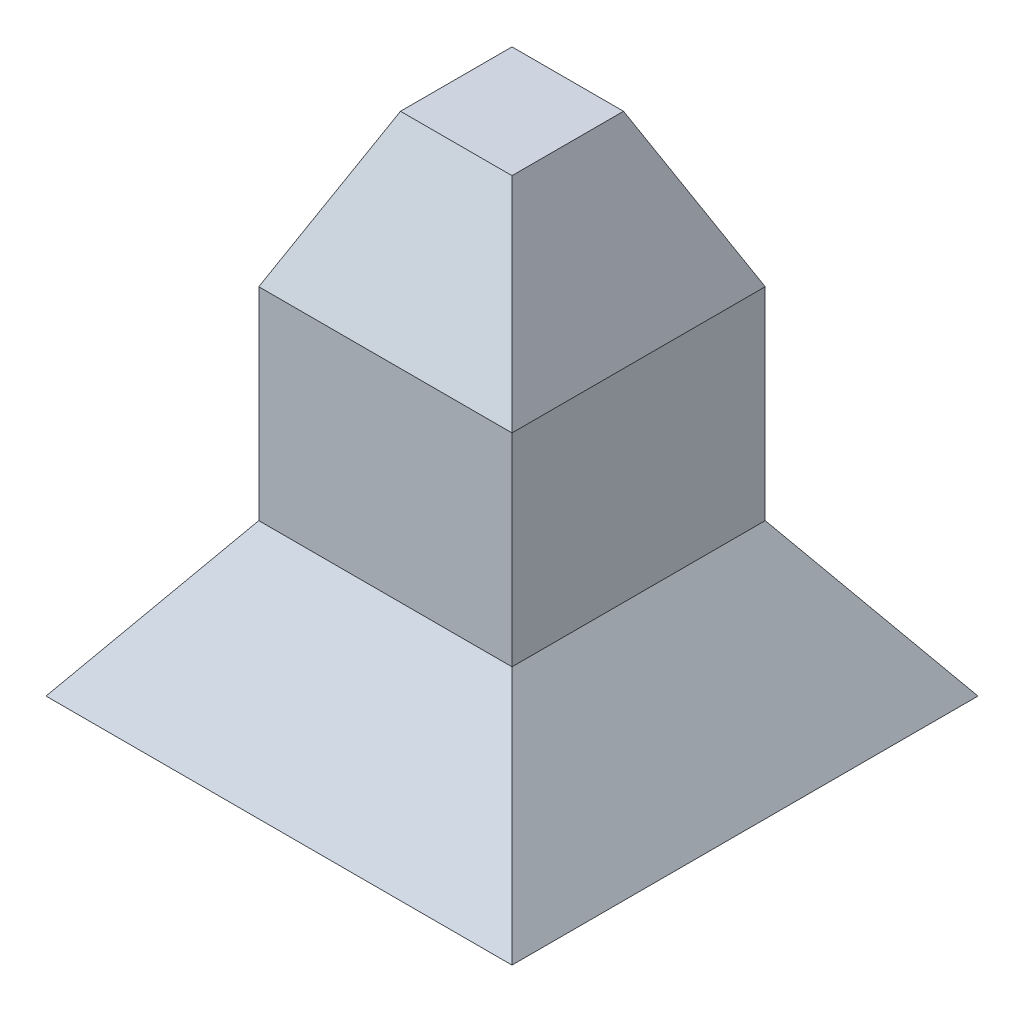
SolidWorks part; units mm, degrees
ref_plane "Front Plane" through (0, 0, 0) normal (0, 0, 1) x (1, 0, 0)
ref_plane "Top Plane" through (0, 0, 0) normal (0, 1, 0) x (1, 0, 0)
ref_plane "Right Plane" through (0, 0, 0) normal (1, 0, 0) x (0, 0, -1)
sketch "Sketch1" plane through (0, 0, 0) normal (0, 1, 0) x (1, 0, 0)
  line L1 (-50, -50) -> (50, -50)
  line L2 (-50, -50) -> (-50, 50)
  line L3 (-50, 50) -> (50, 50)
  line L4 (50, -50) -> (50, 50)
  line L5 (-50, -50) -> (50, 50) construction
  line L6 (-50, 50) -> (50, -50) construction
  point P0 (0, 0)
  dimension "D1" = 100
  dimension "D2" = 100
extrude "Boss-Extrude1" add sketch "Sketch1" along normal blind 80
sketch "Sketch2" plane through (0, 80, 0) normal (0, 1, 0) x (1, 0, 0)
  line L4 (50, -50) -> (50, 50)
  line L5 (50, 50) -> (-50, 50)
  line L6 (-50, 50) -> (-50, -50)
  line L7 (-50, -50) -> (50, -50)
  line L8 (50, -50) -> (50, 50)
  line L9 (50, 50) -> (-50, 50)
  line L10 (-50, 50) -> (-50, -50)
  line L11 (-50, -50) -> (50, -50)
  dimension "D1" = 0
extrude "Boss-Extrude2" add sketch "Sketch2" along normal blind 60 draft 25
sketch "Sketch3" plane through (0, 0, 0) normal (0, -1, 0) x (1, 0, 0)
  line L4 (50, -50) -> (50, 50)
  line L5 (50, 50) -> (-50, 50)
  line L6 (-50, 50) -> (-50, -50)
  line L7 (-50, -50) -> (50, -50)
  line L8 (50, -50) -> (50, 50)
  line L9 (50, 50) -> (-50, 50)
  line L10 (-50, 50) -> (-50, -50)
  line L11 (-50, -50) -> (50, -50)
  dimension "D1" = 0
extrude "Boss-Extrude3" add sketch "Sketch3" along normal blind 60 draft 35 draft outward yes
sketch "Sketch4" plane through (0, -60, 0) normal (0, -1, 0) x (1, 0, 0)
  line L0 (92.0125, 92.0125) -> (-92.0125, 92.0125) construction
  line L1 (-72.0125, -72.0125) -> (72.0125, -72.0125)
  line L2 (-72.0125, -72.0125) -> (-72.0125, 72.0125)
  line L3 (-72.0125, 72.0125) -> (72.0125, 72.0125)
  line L4 (72.0125, -72.0125) -> (72.0125, 72.0125)
  line L5 (-72.0125, -72.0125) -> (72.0125, 72.0125) construction
  line L6 (-72.0125, 72.0125) -> (72.0125, -72.0125) construction
  point P0 (0, 0)
  dimension "D1" = 20
extrude "Cut-Extrude4" cut sketch "Sketch4" against normal blind 20
draft "Draft1" type of draft neutral plane draft angle 35 faces to draft 4 face at (0, -50, -72.0125) face at (72.0125, -50, 0) face at (0, -50, 72.0125) face at (-72.0125, -50, 0) neutral plane through (0, -40, 0) neutral plane normal (0, -1, 0) parameters "D1"=35
sketch "Sketch5" plane through (0, 0, -50) normal (0, 0, -1) x (-1, 0, 0)
  line L0 (50, 0) -> (-50, 80) construction
  line L1 (-50, 0) -> (50, 80) construction
  line L3 (-15, 25) -> (15, 25)
  line L4 (-15, 25) -> (-15, 55)
  line L5 (-15, 55) -> (15, 55)
  line L6 (15, 25) -> (15, 55)
  line L7 (-15, 25) -> (15, 55) construction
  line L8 (-15, 55) -> (15, 25) construction
  point P8 (0, 40)
  dimension "D1" = 30
extrude "Boss-Extrude4" add sketch "Sketch5" along normal blind 20
draft "Draft2" type of draft neutral plane draft angle 20 faces to draft 1 face at (0, 55, -60) neutral plane through (-50, 80, -50) neutral plane normal (0, 0, -1) parameters "D1"=20
